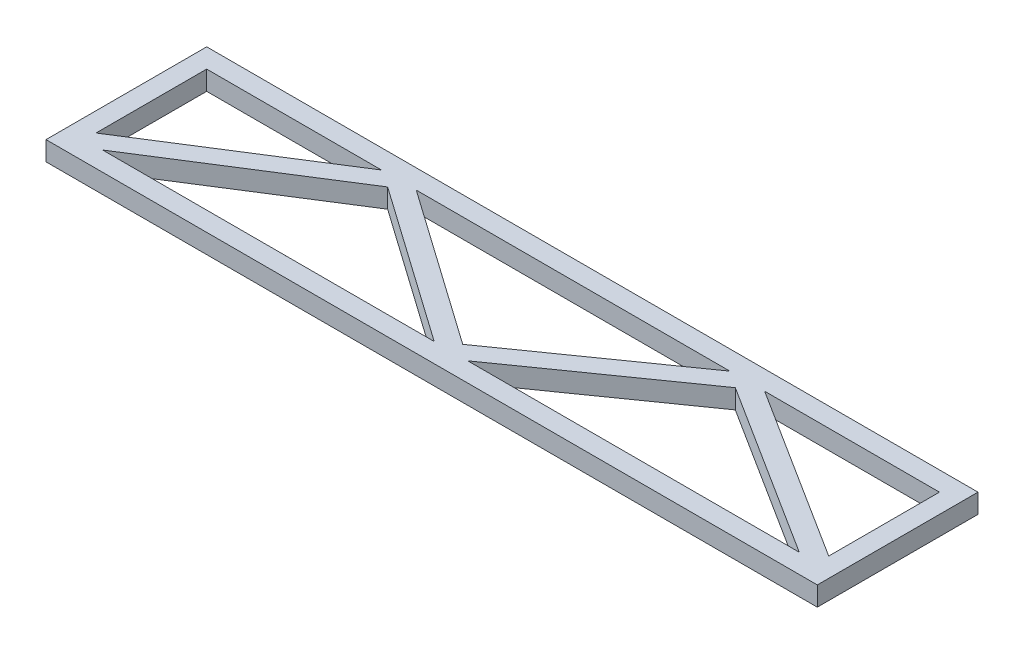
SolidWorks part; units mm, degrees
ref_plane "Front Plane" through (0, 0, 0) normal (0, 0, 1) x (1, 0, 0)
ref_plane "Top Plane" through (0, 0, 0) normal (0, 1, 0) x (1, 0, 0)
ref_plane "Right Plane" through (0, 0, 0) normal (1, 0, 0) x (0, 0, -1)
sketch "Sketch1" plane through (0, 0, 0) normal (0, 1, 0) x (1, 0, 0)
  line L0 (-23.334, -7.7245) -> (-23.334, 9.5)
  line L1 (-26.334, -12.5) -> (93.666, -12.5)
  line L2 (-26.334, -12.5) -> (-26.334, 12.5)
  line L3 (-26.334, 12.5) -> (93.666, 12.5)
  line L4 (93.666, -12.5) -> (93.666, 12.5)
  line L5 (-23.334, 9.5) -> (3.8625, 9.5)
  line L6 (90.666, -7.7245) -> (90.666, 9.5)
  line L7 (-20.5305, -9.5) -> (31.0595, -9.5)
  line L8 (63.4695, 9.5) -> (90.666, 9.5)
  line L9 (60.7099, 7.6967) -> (36.2725, -9.5)
  line L10 (33.666, 21.294) -> (33.666, -23.4092) construction
  line L11 (-20.5305, -9.5) -> (6.6221, 7.6967)
  line L12 (6.6221, 7.6967) -> (31.0595, -9.5)
  line L13 (-23.334, -7.7245) -> (3.8625, 9.5)
  line L14 (9.2725, 9.5) -> (58.0595, 9.5)
  line L15 (87.8625, -9.5) -> (60.7099, 7.6967)
  line L16 (90.666, -7.7245) -> (63.4695, 9.5)
  line L17 (-23.334, -9.5) -> (-23.334, 9.5) construction
  line L18 (-23.334, -9.5) -> (90.666, -9.5) construction
  line L19 (-23.334, 9.5) -> (90.666, 9.5) construction
  line L20 (9.2725, 9.5) -> (33.666, -7.6658)
  line L21 (36.2725, -9.5) -> (87.8625, -9.5)
  line L22 (90.666, -9.5) -> (90.666, 9.5) construction
  line L23 (58.0595, 9.5) -> (33.666, -7.6658)
  dimension "D1" = 25
  dimension "D2" = 120
extrude "Boss-Extrude1" add sketch "Sketch1" along normal blind 3
